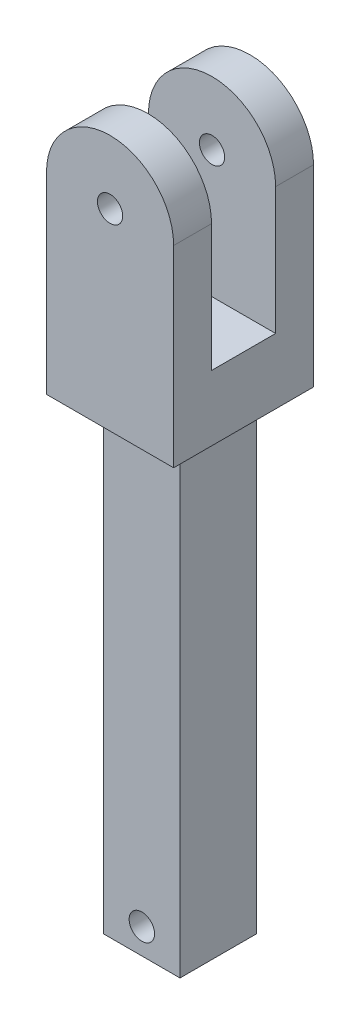
SolidWorks part; units mm, degrees
ref_plane "前基準面" through (0, 0, 0) normal (0, 0, 1) x (1, 0, 0)
ref_plane "上基準面" through (0, 0, 0) normal (0, 1, 0) x (1, 0, 0)
ref_plane "右基準面" through (0, 0, 0) normal (1, 0, 0) x (0, 0, -1)
sketch "草圖1" plane through (0, 0, 0) normal (0, 0, 1) x (1, 0, 0)
  line L0 (0, 0) -> (0, -11.05)
  line L1 (-10, 0) -> (-10, -30.2764)
  line L3 (10, -30.2764) -> (10, 0)
  line L4 (-10, -30.2764) -> (10, -30.2764)
  circle A1 centre (0, 0) radius 1.985
  arc A2 (10, 0) -> (-10, 0) centre (0, 0) ccw
  dimension "D1" = 11.05
  dimension "D2" = 3.97
  dimension "D3" = 20
extrude "填料-伸長1" add sketch "草圖1" along normal blind 12
sketch "草圖2" plane through (10, 0, 0) normal (1, 0, 0) x (0, 0, -1)
  line L0 (-12, 0) -> (-9.1, 0)
  line L1 (-12, 0) -> (0, 0) construction
  line L2 (-12, 10) -> (-12, 0) construction
  line L3 (0, 0) -> (-2.9, 0)
  line L4 (-6, 0) -> (-3, 0)
  line L5 (-6, 0) -> (-9, 0)
  line L6 (-9, 0) -> (-9, 15.7808)
  line L7 (-9, 15.7808) -> (-3, 15.7808)
  line L8 (-3, 15.7808) -> (-3, 0)
  line L9 (-3, 0) -> (-3, -20)
  line L10 (-9, 0) -> (-8.6005, -20)
  line L11 (-8.6005, -20) -> (-3, -20)
  line M8 (0, 0) -> (-12, 0)
  dimension "D1" = 2.9
  dimension "D2" = 2.9
  dimension "D3" = 3
  dimension "D4" = 3
  dimension "D5" = 20
extrude "除料-伸長1" cut sketch "草圖2" against normal through all contours L8 L7 L6 M8 | L10 L11 L9 M8
sketch "草圖11" plane through (10, 0, 0) normal (1, 0, 0) x (0, 0, -1)
  line L0 (-9, 0) -> (-9, -20)
  line L1 (-9, -20) -> (-8.6005, -20)
  line L2 (-9, 0) -> (-8.6005, -20)
extrude "除料-伸長6" cut sketch "草圖11" against normal through all
sketch "草圖12" plane through (0, 0, 12) normal (0, 0, 1) x (1, 0, 0)
  line L0 (-10, 0) -> (-10, -30.2764)
  line L1 (-10, -30.2764) -> (10, -30.2764)
  line L2 (10, -30.2764) -> (10, 0)
  circle A0 centre (0, 0) radius 1.45
  circle A1 centre (0, 0) radius 10
  circle M1 centre (0, 0) radius 1.985
  line M2 (10, -30.2764) -> (10, 0)
  arc M3 (10, 0) -> (-10, 0) centre (0, 0) ccw
  line M4 (-10, 0) -> (-10, -30.2764)
  line M5 (-10, -30.2764) -> (10, -30.2764)
extrude "填料-伸長11" add sketch "草圖12" along normal blind 5 contours A1 M3 M1 | A1 M4 M5 M2
sketch "草圖13" plane through (0, 0, 0) normal (0, 0, -1) x (-1, 0, 0)
  line L0 (-10, 0) -> (-10, -30.2764)
  line L1 (-10, -30.2764) -> (10, -30.2764)
  line L2 (10, 0) -> (10, -30.2764) construction
  line L3 (10, -30.2764) -> (-10, -30.2764) construction
  line L4 (10, -30.2764) -> (10, 0)
  circle A0 centre (0, 0) radius 1.45
  circle A1 centre (0, 0) radius 10
  circle M1 centre (0, 0) radius 1.985
  line M2 (-10, 0) -> (-10, -30.2764)
  line M3 (-10, -30.2764) -> (10, -30.2764)
  line M4 (10, -30.2764) -> (10, 0)
  arc M5 (10, 0) -> (-10, 0) centre (0, 0) ccw
extrude "填料-伸長12" add sketch "草圖13" along normal blind 5 contours A1 M5 M1 | A1 M2 M3 M4
sketch "草圖14" plane through (-10, 0, 0) normal (-1, 0, 0) x (0, 0, 1)
  line L0 (3, -20) -> (0.96, -20)
  line L1 (0.96, -20) -> (0.96, 10)
  line L2 (3, 10) -> (-5, 10) construction
  line L3 (0.96, 10) -> (3, 10)
  line L5 (3, 10) -> (11.04, 10)
  line L6 (9, -20) -> (11.04, -20)
  line L7 (11.04, -20) -> (11.04, 10)
  line L8 (17, 10) -> (9, 10) construction
  line L9 (0.96, 10) -> (11.04, 10)
  line L10 (11.04, -20) -> (0.96, -20)
  line L11 (0.96, 10) -> (0.96, -20)
  line L12 (0.96, 10) -> (11.04, 10)
  line M7 (9, 0) -> (9, -20)
  line M8 (9, -20) -> (3, -20)
  line M9 (3, -20) -> (3, 0)
  line M10 (3, 0) -> (-5, 0)
  line M14 (17, 0) -> (9, 0)
  dimension "D1" = 2.04
  dimension "D2" = 2.04
extrude "除料-伸長7" cut sketch "草圖14" against normal through all contours L7 L5 L3 L1 M14 M10 M9 M8 M7 | L1 L0 M9 M10 | L6 L7 M14 M7
sketch "草圖15" plane through (0, -30.2764, 0) normal (0, -1, 0) x (1, 0, 0)
  line L0 (-10, 6) -> (10, 6)
  line L1 (-10, 17) -> (-10, -5) construction
  line L2 (10, 17) -> (10, -5) construction
  line L3 (0, 17) -> (0, -5)
  line L4 (-10, 17) -> (10, 17) construction
  line L5 (10, -5) -> (-10, -5) construction
  line L7 (-6, 0) -> (6, 0)
  line L8 (-6, 0) -> (-6, 12)
  line L9 (-6, 12) -> (6, 12)
  line L10 (6, 0) -> (6, 12)
  line L11 (-6, 0) -> (6, 12) construction
  line L12 (-6, 12) -> (6, 0) construction
  point P12 (0, 6)
  dimension "D1" = 12
  dimension "D2" = 12
extrude "填料-伸長13" add sketch "草圖15" along normal blind 74 contours L0 L10 L9 L3 | L9 L8 L0 L3 | L7 L10 L0 L3 | L8 L7 L3 L0
sketch "草圖17" plane through (0, 0, 0) normal (0, 0, -1) x (-1, 0, 0)
  line L0 (0, -104.2764) -> (0, -100.2764)
  line L1 (6, -104.2764) -> (-6, -104.2764) construction
  circle A0 centre (0, -100.2764) radius 2
  dimension "D2" = 4
  dimension "D1" = 4
extrude "除料-伸長8" cut sketch "草圖17" against normal through all
